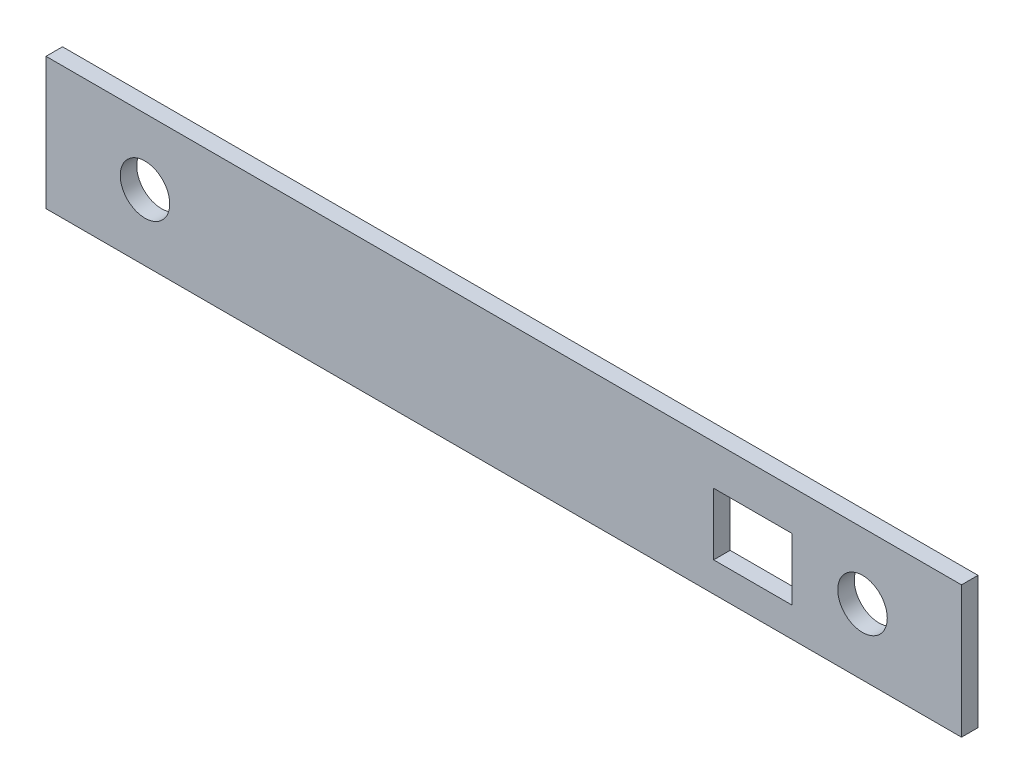
SolidWorks part; units mm, degrees
ref_plane "Front Plane" through (0, 0, 0) normal (0, 0, 1) x (1, 0, 0)
ref_plane "Top Plane" through (0, 0, 0) normal (0, 1, 0) x (1, 0, 0)
ref_plane "Right Plane" through (0, 0, 0) normal (1, 0, 0) x (0, 0, -1)
sketch "Sketch1" plane through (0, 0, 0) normal (0, 0, 1) x (1, 0, 0)
  line L0 (0, 25.4) -> (352.425, 25.4) construction
  line L1 (0, 0) -> (352.425, 0)
  line L2 (0, 0) -> (0, 50.8)
  line L3 (0, 50.8) -> (352.425, 50.8)
  line L4 (352.425, 0) -> (352.425, 50.8)
  line L6 (257.0064, 11.4236) -> (287.1522, 11.4236)
  line L7 (257.0064, 11.4236) -> (257.0064, 35.3058)
  line L8 (257.0064, 35.3058) -> (287.1522, 35.3058)
  line L9 (287.1522, 11.4236) -> (287.1522, 35.3058)
  circle A0 centre (38.1, 25.4) radius 9.525
  circle A1 centre (314.325, 25.4) radius 9.525
  dimension "D2" = 38.1
  dimension "D5" = 19.05
  dimension "D1" = 50.8
  dimension "D3" = 38.1
  dimension "D4" = 276.225
extrude "Boss-Extrude1" add sketch "Sketch1" along normal blind 6.35
sketch "Sketch2" plane through (0, 0, 0) normal (0, -1, 0) x (1, 0, 0)
  circle A0 centre (238.7592, 3.175) radius 1.7762 construction
  circle A1 centre (238.7592, 3.175) radius 1.7762
extrude "Cut-Extrude1" cut sketch "Sketch2" against normal blind 19.304
